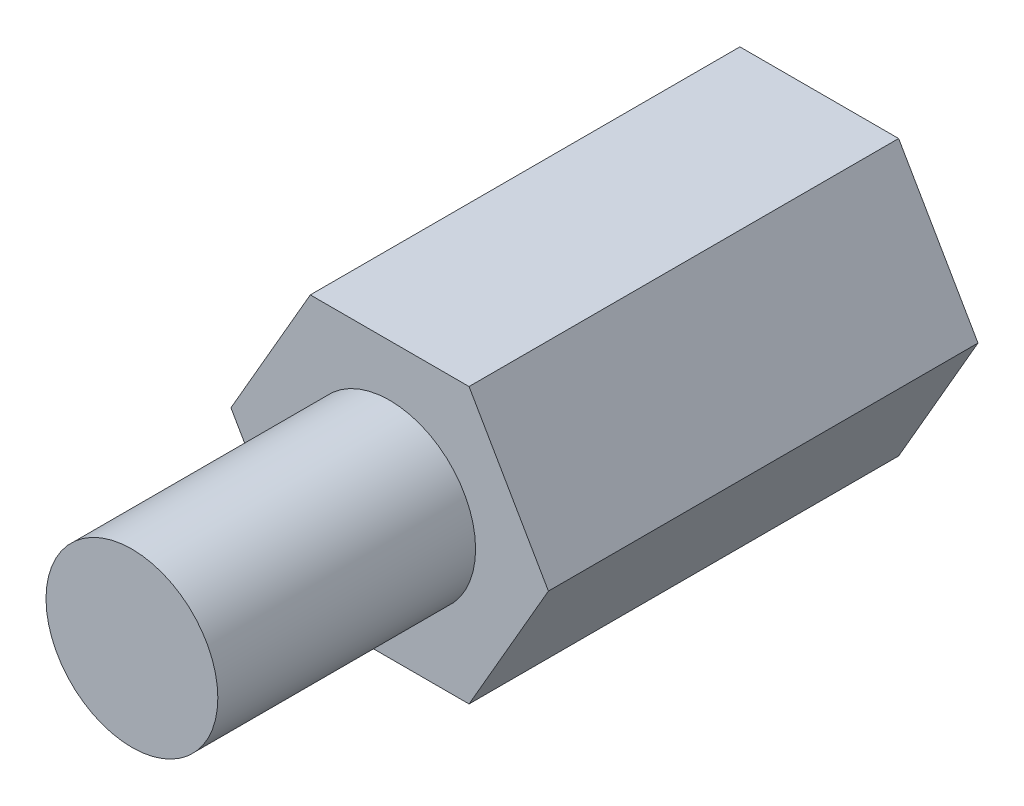
SolidWorks part; units mm, degrees
ref_plane "前视基准面" through (0, 0, 0) normal (0, 0, 1) x (1, 0, 0)
ref_plane "上视基准面" through (0, 0, 0) normal (0, 1, 0) x (1, 0, 0)
ref_plane "右视基准面" through (0, 0, 0) normal (1, 0, 0) x (0, 0, -1)
sketch "草图1" plane through (0, 0, 0) normal (0, 0, 1) x (1, 0, 0)
  line L0 (-28.6627, 0) -> (33.6774, 0) construction
  line L1 (0.9238, -1.6) -> (1.8475, 0)
  line L2 (1.8475, 0) -> (0.9238, 1.6)
  line L3 (0.9238, 1.6) -> (-0.9238, 1.6)
  line L4 (-0.9238, 1.6) -> (-1.8475, 0)
  line L5 (-1.8475, 0) -> (-0.9238, -1.6)
  line L6 (-0.9238, -1.6) -> (0.9238, -1.6)
  circle A0 centre (0, 0) radius 1.6 construction
  dimension "D1" = 3.2
extrude "拉伸1" add sketch "草图1" along normal blind 5
sketch "草图2" plane through (0, 0, 5) normal (0, 0, 1) x (1, 0, 0)
  circle A0 centre (0, 0) radius 1
  dimension "D1" = 2
extrude "拉伸2" add sketch "草图2" along normal blind 3
hole_wizard "M2 螺纹孔1" positions "3D草图2" profile "草图5" tap size "M2" standard "Iso"
sketch3d "3D草图2"
  point P0 (0, 0, 0)
  point P2 (0, 0, 0)
  point P3 (0, 0, 0)
  point P4 (0, 0, 0)
cosmetic thread "孔螺蚊线1" parameters "D1"=4, "D2"=2
sketch "草图5" plane through (0, 0, 0) normal (1, 0, 0) x (0, 1, 0)
  line L0 (0, 0) -> (0, 6.4807)
  line L1 (0, 6.4807) -> (0.8, 6)
  line L2 (0.8, 6) -> (0.8, 0)
  line L5 (0.8, 0) -> (0, 0)
  line L10 (0, 6.4807) -> (-0.8, 6) construction
  line L11 (0, -6.35) -> (0, 107.95) construction
  dimension "蹟恇謂郰芛眻噤" = 1.6
  dimension "蹟恇謂郰芛旮僅" = 6
  dimension "絳芛褒僅" = 118
cosmetic thread "孔螺蚊线2" parameters "D1"=4, "D2"=2
cosmetic thread "孔螺蚊线3" parameters "D1"=4, "D2"=2
cosmetic thread "孔螺蚊线4" parameters "D1"=4, "D2"=2
sketch "草图6" plane through (0, 0, 0) normal (0, 0, -1) x (-1, 0, 0)
  circle A0 centre (0, 0) radius 1.5
  dimension "D1" = 3
extrude "拉伸3" [suppressed] add sketch "草图6" along normal blind 10
